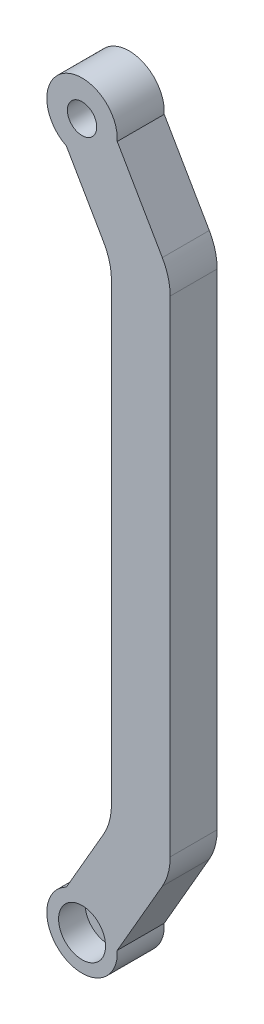
SolidWorks part; units mm, degrees
material "Vero PureWhite"
ref_plane "前视基准面" through (0, 0, 0) normal (0, 0, 1) x (1, 0, 0)
ref_plane "上视基准面" through (0, 0, 0) normal (0, 1, 0) x (1, 0, 0)
ref_plane "右视基准面" through (0, 0, 0) normal (1, 0, 0) x (0, 0, -1)
other "Configuration Table"
sketch "草图1" plane through (0, 0, 0) normal (0, 0, 1) x (1, 0, 0)
  line L0 (0, 0) -> (0, 120) construction
  circle A0 centre (0, 0) radius 6
  circle A1 centre (0, 120) radius 6
  dimension "D2" = 12
  dimension "D3" = 12
  dimension "D1" = 120
extrude "凸台-拉伸1" add sketch "草图1" along normal blind 8
sketch "草图2" plane through (0, 0, 0) normal (0, 0, 1) x (1, 0, 0)
  line L0 (0, 120) -> (0, 0) construction
  line L1 (0, 120) -> (10, 102.6795)
  line L2 (10, 102.6795) -> (10, 17.3205)
  line L3 (10, 17.3205) -> (0, 0)
  dimension "D1" = 10
  dimension "D2" = 30
extrude "拉伸-薄壁1" add sketch "草图2" along normal up to surface (8 mm away) thin up to face at (6, 120, 8) thin type mid plane wall 10
sketch "草图3" plane through (0, 0, 8) normal (0, 0, 1) x (1, 0, 0)
  circle A1 centre (0, 120) radius 2.5
extrude "切除-拉伸1" cut sketch "草图3" against normal through all
sketch "草图4" plane through (0, 0, 8) normal (0, 0, 1) x (1, 0, 0)
  circle A0 centre (0, 0) radius 2
  dimension "D1" = 4
extrude "切除-拉伸2" cut sketch "草图4" against normal through all
sketch "草图5" plane through (0, 0, 8) normal (0, 0, 1) x (1, 0, 0)
  circle A0 centre (0, 0) radius 4
  dimension "D1" = 8
extrude "切除-拉伸3" cut sketch "草图5" against normal blind 4.5
fillet "圆角1" radius 10 4 edges at (5, 18.6603, 4) (5, 101.3397, 4) (15, 104.0192, 4) (15, 15.9808, 4)
